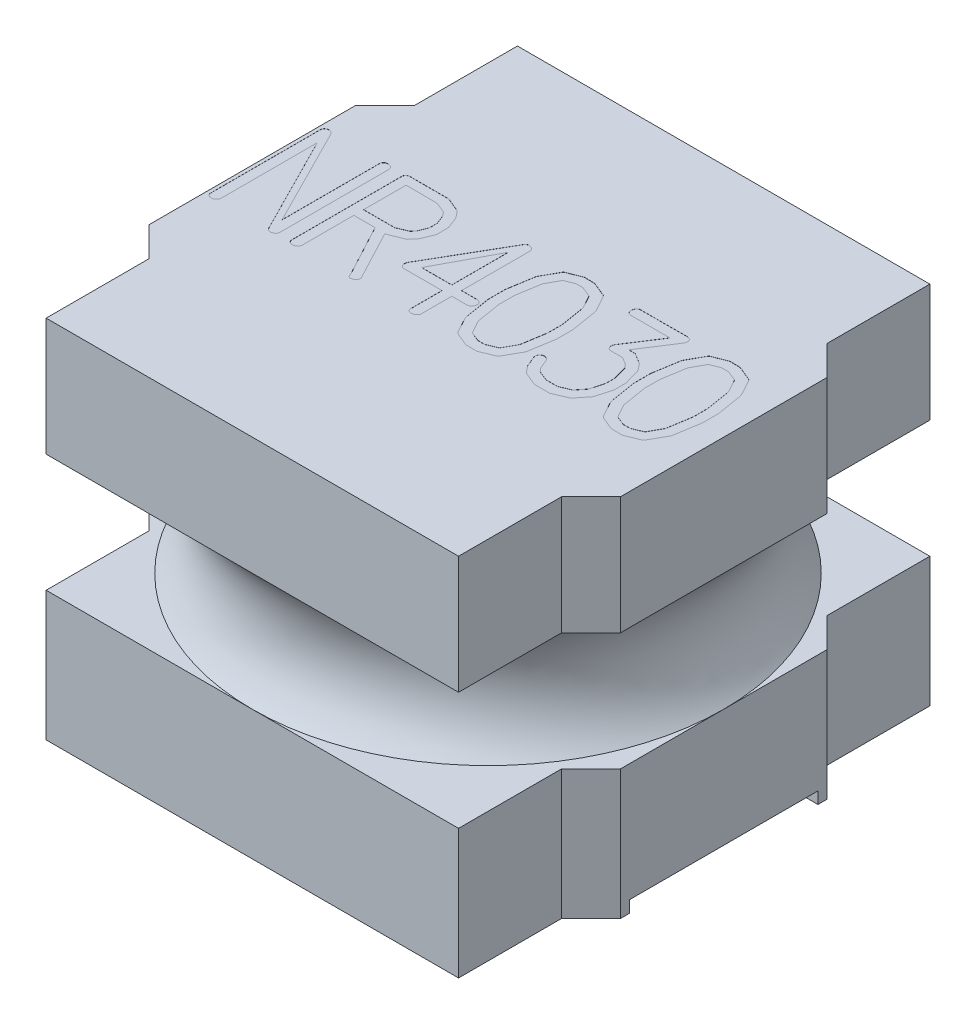
SolidWorks part; units mm, degrees
ref_plane "Front Plane" through (0, 0, 0) normal (0, 0, 1) x (1, 0, 0)
ref_plane "Top Plane" through (0, 0, 0) normal (0, 1, 0) x (1, 0, 0)
ref_plane "Right Plane" through (0, 0, 0) normal (1, 0, 0) x (0, 0, -1)
sketch "Sketch1" plane through (0, 0, 0) normal (0, 1, 0) x (1, 0, 0)
  line L0 (-2, 0) -> (2, 0) construction
  line L1 (-1.75, 2) -> (1.75, 2)
  line L2 (-2, 0.875) -> (-2, -0.875)
  line L3 (-1.75, -2) -> (1.75, -2)
  line L4 (2, 0.875) -> (2, -0.875)
  line L5 (-1.75, 1.75) -> (1.75, -1.75) construction
  line L6 (-1.75, -1.75) -> (1.75, 1.75) construction
  line L7 (0, 2) -> (0, -2) construction
  line L8 (-1.75, 2) -> (-1.75, 1.125)
  line L9 (-1.75, 1.125) -> (-2, 0.875)
  line L10 (1.75, 2) -> (1.75, 1.125)
  line L11 (1.75, 1.125) -> (2, 0.875)
  line L12 (1.75, -2) -> (1.75, -1.125)
  line L13 (1.75, -1.125) -> (2, -0.875)
  line L14 (-1.75, -1.125) -> (-2, -0.875)
  line L15 (-1.75, -2) -> (-1.75, -1.125)
  line L16 (-2, -0.875) -> (-2, -2) construction
  line L17 (-2, -2) -> (-1.75, -1.75) construction
  line L18 (-2, -2) -> (-1.75, -2) construction
  line L19 (1.75, -2) -> (2, -2) construction
  line L20 (1.75, -1.75) -> (2, -2) construction
  line L21 (2, -0.875) -> (2, -2) construction
  line L22 (2, 2) -> (2, 0.875) construction
  line L23 (1.75, 1.75) -> (2, 2) construction
  line L24 (1.75, 2) -> (2, 2) construction
  line L25 (-2, 2) -> (-1.75, 2) construction
  line L26 (-2, 2) -> (-1.75, 1.75) construction
  line L27 (-2, 2) -> (-2, 0.875) construction
  point P0 (0, 0)
  dimension "D1" = 4
  dimension "D2" = 3.5
  dimension "D3" = 1.75
  dimension "D4" = 135
  dimension "D5" = 4
extrude "Boss-Extrude1" add sketch "Sketch1" along normal blind 1 from offset 1.5 offset against normal yes
sketch "Sketch2" plane through (0, 0, 0) normal (1, 0, 0) x (0, 0, -1)
  line L0 (0, -1.5) -> (0, 0) construction
  line L1 (-0.875, -1.5) -> (0.875, -1.5) construction
  line L2 (-2, 0.5) -> (0, 0.5)
  line L3 (0, 0.5) -> (0, -0.5)
  line L4 (0, -0.5) -> (-2, -0.5)
  arc A0 (-2, -0.5) -> (-2, 0.5) centre (-2.559, 0) ccw
  dimension "D2" = 0.75
  dimension "D1" = 1
revolve "Revolve1" add sketch "Sketch2" angle 360 about L0
mirror "Mirror1" about plane through (0, 0, 0) normal (0, 1, 0) of "Boss-Extrude1"
sketch "Sketch3" plane through (0, 1.5, 0) normal (0, 1, 0) x (1, 0, 0)
  line L0 (-2, -0.3915) -> (2, -0.3915) construction
  text T0 "NR4030" font "SWSimp" height 1
extrude "Cut-Extrude1" cut sketch "Sketch3" against normal blind 0.001
sketch "Sketch4" plane through (0, -1.5, 0) normal (0, -1, 0) x (1, 0, 0)
  line L0 (-2, 0.8) -> (2, 0.8)
  line L1 (-2, -0.875) -> (-2, 0.875) construction
  line L2 (2, 0.875) -> (2, -0.875) construction
  line L3 (0, 0) -> (2.4671, 0) construction
  line L4 (2, 0.8) -> (2, 0.875)
  line L5 (2, 0.875) -> (1.75, 1.125)
  line L6 (1.75, 1.125) -> (1.75, 2)
  line L7 (1.75, 2) -> (-1.75, 2)
  line L8 (-1.75, 2) -> (-1.75, 1.125)
  line L9 (-1.75, 1.125) -> (-2, 0.875)
  line L10 (-2, 0.875) -> (-2, 0.8)
  line L11 (-1.75, -1.125) -> (-2, -0.875)
  line L12 (-1.75, -2) -> (-1.75, -1.125)
  line L13 (1.75, -2) -> (-1.75, -2)
  line L14 (1.75, -1.125) -> (1.75, -2)
  line L15 (2, -0.875) -> (1.75, -1.125)
  line L16 (2, -0.8) -> (2, -0.875)
  line L17 (-2, -0.8) -> (2, -0.8)
  line L18 (-2, -0.875) -> (-2, -0.8)
  dimension "D1" = 0.8
extrude "Boss-Extrude2" add sketch "Sketch4" along normal blind 0.1
